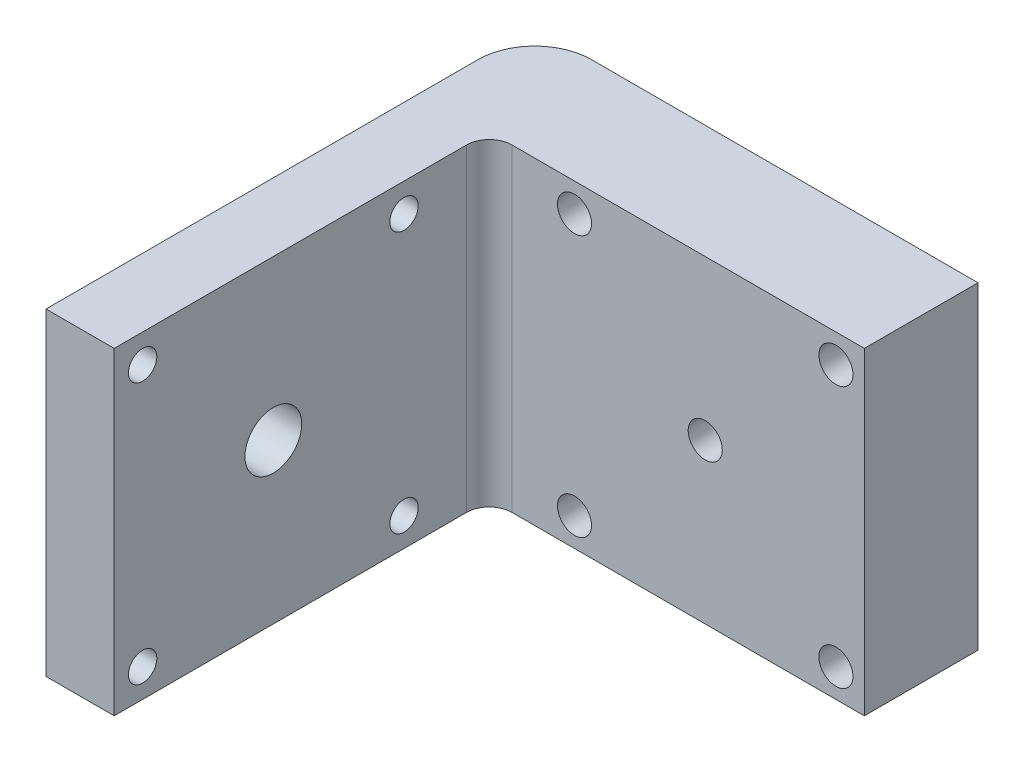
SolidWorks part; units mm, degrees
ref_plane "前视基准面" through (0, 0, 0) normal (0, 0, 1) x (1, 0, 0)
ref_plane "上视基准面" through (0, 0, 0) normal (0, 1, 0) x (1, 0, 0)
ref_plane "右视基准面" through (0, 0, 0) normal (1, 0, 0) x (0, 0, -1)
sketch "草图1" plane through (0, 0, 0) normal (0, 0, 1) x (1, 0, 0)
  line L1 (-14, 14) -> (14, 14)
  line L2 (-14, 14) -> (-14, -14)
  line L3 (-14, -14) -> (14, -14)
  line L4 (14, 14) -> (14, -14)
  line L5 (-14, 14) -> (14, -14) construction
  line L6 (-14, -14) -> (14, 14) construction
  line L11 (-14, 14) -> (-19, 14)
  line L12 (-14, 14) -> (-14, -14)
  line L13 (-14, -14) -> (-19, -14)
  line L14 (-19, 14) -> (-19, -14)
  circle A0 centre (-11.5, 11.5) radius 1.5
  circle A1 centre (11.5, 11.5) radius 1.5
  circle A2 centre (-11.5, -11.5) radius 1.5
  circle A3 centre (11.5, -11.5) radius 1.5
  circle A4 centre (0, 0) radius 1.5
  point P0 (0, 0)
  dimension "D7" = 3
  dimension "D1" = 28
  dimension "D2" = 28
  dimension "D3" = 23
  dimension "D4" = 5
extrude "凸台-拉伸1" add sketch "草图1" along normal blind 10 contours L11 L14 L13 L2 | L4 L1 L2 L3 A4 A3 A2 A1 A0
sketch "草图3" plane through (-19, 0, 0) normal (-1, 0, 0) x (0, 0, 1)
  line L0 (15, 14) -> (43, -14)
  line L1 (10, 14) -> (15, 14)
  line L2 (10, 14) -> (10, -14)
  line L3 (10, -14) -> (15, -14)
  line L4 (0, 14) -> (0, -14)
  line L5 (0, -14) -> (10, -14)
  line L6 (10, -14) -> (10, 14)
  line L7 (10, 14) -> (0, 14)
  line L8 (0, 14) -> (0, -14)
  line L9 (0, -14) -> (10, -14)
  line L10 (10, -14) -> (10, 14)
  line L11 (10, 14) -> (0, 14)
  line L12 (15, 14) -> (15, -14)
  line L13 (15, 14) -> (43, 14)
  line L14 (15, 14) -> (15, -14)
  line L15 (15, -14) -> (43, -14)
  line L16 (43, 14) -> (43, -14)
  line L17 (43, 14) -> (15, -14)
  circle A0 centre (17.5, 11.5) radius 1.25
  circle A1 centre (40.5, 11.5) radius 1.25
  circle A2 centre (17.5, -11.5) radius 1.25
  circle A3 centre (40.5, -11.5) radius 1.25
  circle A4 centre (29, 0) radius 2.5
  line M19 (0, 14) -> (0, -14)
  line M20 (0, -14) -> (10, -14)
  line M21 (10, -14) -> (10, 14)
  line M22 (10, 14) -> (0, 14)
  dimension "D5" = 2.5
  dimension "D6" = 5
  dimension "D2" = 5
  dimension "D3" = 28
  dimension "D4" = 23
  dimension "D1" = 0
extrude "凸台-拉伸3" add sketch "草图3" along normal blind 6 contours M22 M19 M20 M21 | L12 L1 L3 M21 | A4 L0 A0 L12 L17 A2 | A4 L17 A1 L13 L0 A0 | A4 L0 A3 L16 L17 A1 | A4 L17 A2 L15 L0 A3
fillet "圆角3" radius 5 1 edges at (-25, 0, 0)
fillet "圆角4" radius 2 1 edges at (-19, 0, 10)
